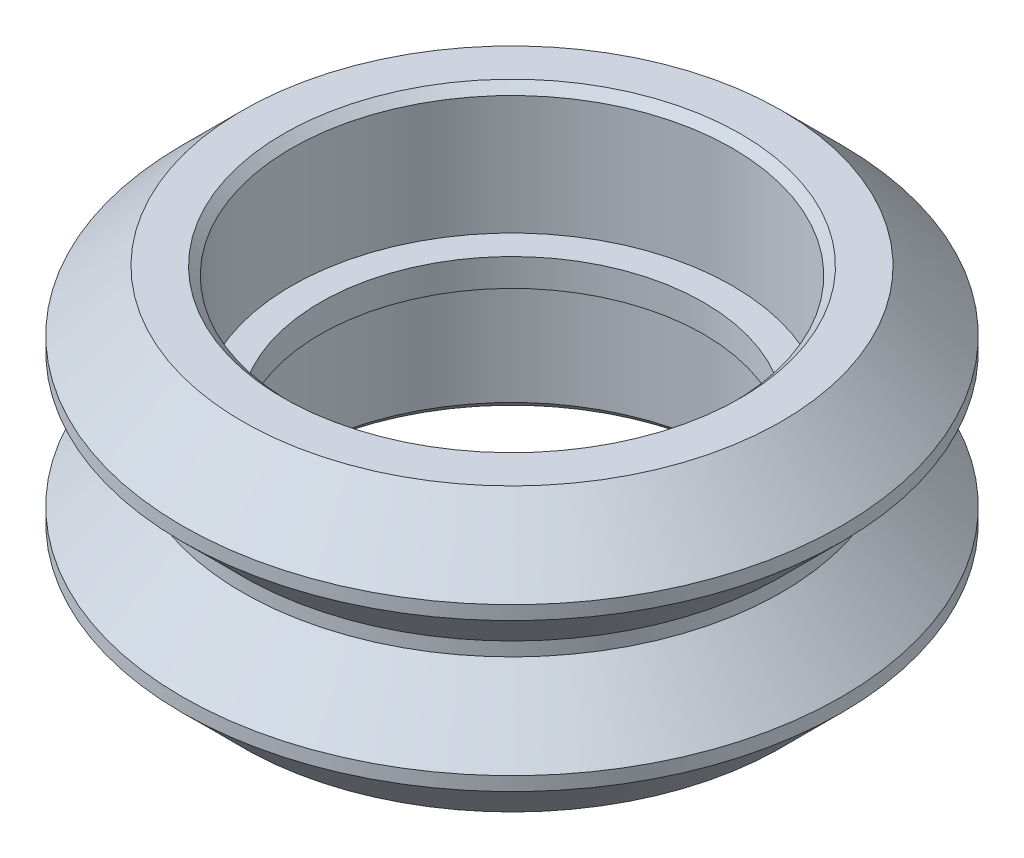
SolidWorks part; units mm, degrees
material "5052-O, Barre (SS)"
ref_plane "Plan de face" through (0, 0, 0) normal (0, 0, 1) x (1, 0, 0)
ref_plane "Plan de dessus" through (0, 0, 0) normal (0, 1, 0) x (1, 0, 0)
ref_plane "Plan de droite" through (0, 0, 0) normal (1, 0, 0) x (0, 0, -1)
sketch "Esquisse1" plane through (0, 0, 0) normal (0, 0, 1) x (1, 0, 0)
  line L0 (0, 0) -> (0, 10.23) construction
  line L1 (7.987, 9.93) -> (7.987, 5.615)
  line L2 (8.287, 10.23) -> (9.7625, 10.23)
  line L3 (9.7625, 10.23) -> (11.945, 8.0475)
  line L4 (11.945, 8.0475) -> (11.945, 7.5475)
  line L5 (9.7625, 5.365) -> (9.7625, 4.865)
  line L6 (7.987, 5.115) -> (9.7625, 5.115) construction
  line L7 (11.945, 7.5475) -> (9.7625, 5.365)
  line L8 (11.945, 8.0475) -> (12.195, 7.7975) construction
  line L9 (12.195, 7.7975) -> (11.945, 7.5475) construction
  line L10 (7.987, 5.615) -> (6.945, 5.615)
  line L11 (6.945, 5.615) -> (6.945, 4.615)
  line L12 (0, 5.115) -> (7.987, 5.115) construction
  line L13 (8.287, 10.23) -> (7.987, 9.93)
  line L14 (7.987, 4.615) -> (6.945, 4.615)
  line L15 (7.987, 0.3) -> (7.987, 4.615)
  line L16 (8.287, 0) -> (7.987, 0.3)
  line L17 (8.287, 0) -> (9.7625, 0)
  line L18 (9.7625, 0) -> (11.945, 2.1825)
  line L19 (11.945, 2.1825) -> (11.945, 2.6825)
  line L20 (11.945, 2.6825) -> (9.7625, 4.865)
  point P4 (7.987, 10.23)
  point P18 (6.945, 5.115)
  dimension "D1" = 10.23
  dimension "D2" = 45
  dimension "D3" = 0.5
  dimension "D4" = 0.25
  dimension "D5" = 24.39
  dimension "D6" = 1
  dimension "D7" = 15.974
  dimension "D8" = 13.89
revolve "Révolution1" add sketch "Esquisse1" angle 360 about L0
